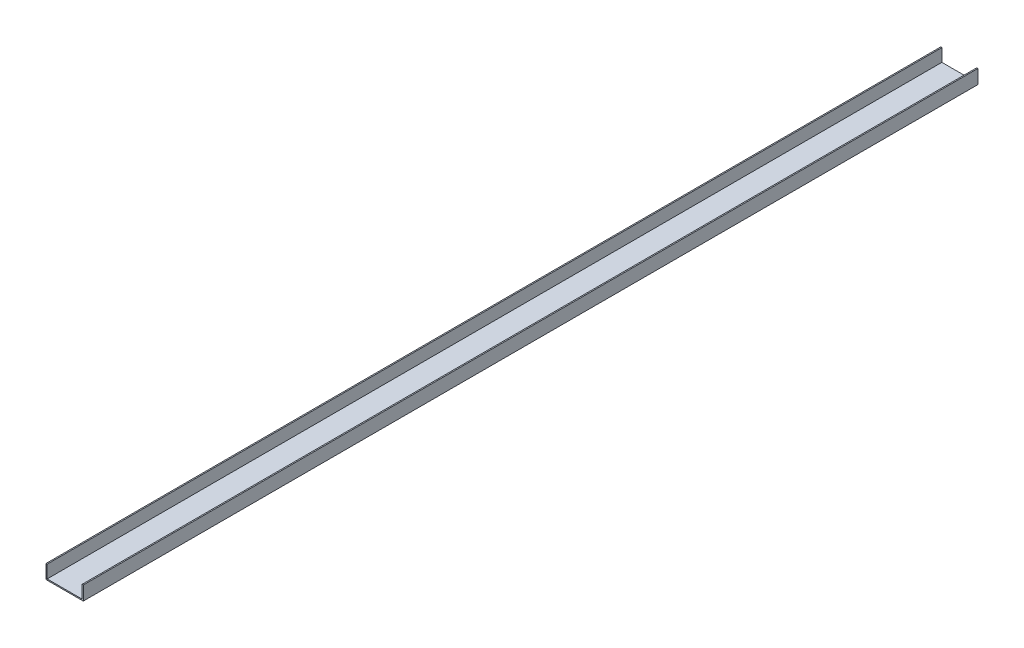
SolidWorks part; units mm, degrees
ref_plane "Front" through (0, 0, 0) normal (0, 0, 1) x (1, 0, 0)
ref_plane "Top" through (0, 0, 0) normal (0, 1, 0) x (1, 0, 0)
ref_plane "Right" through (0, 0, 0) normal (1, 0, 0) x (0, 0, -1)
sketch "Sketch1" plane through (0, 0, 0) normal (0, 0, 1) x (1, 0, 0)
  line L0 (0, -9.525) -> (0, 9.525) construction
  line L1 (-25.4, 0) -> (25.4, 0) construction
  line L2 (23.8125, 9.525) -> (-23.8125, 9.525) construction
  line L3 (-25.4, -9.525) -> (25.4, -9.525)
  line L4 (-25.4, -9.525) -> (-25.4, 9.525)
  line L5 (-25.4, 9.525) -> (25.4, 9.525)
  line L6 (25.4, -9.525) -> (25.4, 9.525)
  line L7 (-25.4, -9.525) -> (25.4, 9.525) construction
  line L8 (-25.4, 9.525) -> (25.4, -9.525) construction
  line L9 (-23.8125, -9.525) -> (23.8125, -9.525)
  point P3 (0, 0)
  point P4 (0, 0)
  point P8 (0, 0)
  point P13 (25.4, -7.9375)
  point P17 (0, 9.525)
  point P20 (0, -9.525)
  dimension "Outside Width" = 50.8
  dimension "Outside Height" = 19.05
  dimension "Inside Height" = 17.4625
  dimension "Wall Thickness" = 1.5875
  dimension "Inside Width" = 47.625
sketch "Sketch2" plane through (0, 0, 0) normal (1, 0, 0) x (0, 0, -1)
  line L0 (-609.6, 0) -> (609.6, 0) construction
  dimension "Length" = 1219.2
sketch "Sketch3" plane through (0, 0, 0) normal (0, 0, 1) x (1, 0, 0)
  line L0 (-25.4, 9.525) -> (-25.4, -9.525)
  line L1 (-25.4, -9.525) -> (25.4, -9.525)
  line L2 (25.4, -9.525) -> (25.4, 9.525)
  line L3 (25.4, 9.525) -> (23.8125, 9.525)
  line L4 (23.8125, 9.525) -> (23.8125, -7.9375)
  line L5 (23.8125, -7.9375) -> (-23.8125, -7.9375)
  line L6 (-23.8125, -7.9375) -> (-23.8125, 9.525)
  line L7 (-23.8125, 9.525) -> (-25.4, 9.525)
  line L8 (-23.8125, -7.9375) -> (-23.8125, -9.525) construction
  dimension "D1" = 19.05
  dimension "D2" = 50.8
  dimension "D3" = 1.5875
extrude "Boss-Extrude2" add sketch "Sketch3" along normal mid plane 1219.2
sketch "Reference Sketch1" plane through (0, 0, 0) normal (1, 0, 0) x (0, 0, -1)
  line L0 (-609.6, 0) -> (609.6, 0) construction
  point P0 (-576.2625, 0)
  point P1 (576.2625, 0)
  dimension "D1" = 33.3375
  dimension "D2" = 33.3375
equation "\"D1@Sketch3\" = \"Outside Height@Sketch1\""
equation "\"D2@Sketch3\" = \"Outside Width@Sketch1\""
equation "\"D3@Sketch3\" = \"Wall Thickness@Sketch1\""
equation "\"D1@Reference Sketch1\"=\"Outside Height@Sketch1\" * 1.75"
equation "\"D2@Reference Sketch1\" = \"D1@Reference Sketch1\""
equation "\"D1@Boss-Extrude2\" = \"Length@Sketch2\""
equation "\"Inside Height@Sketch1\"=\"Outside Height@Sketch1\"-\"Wall Thickness@Sketch1\""
equation "\"Inside Width@Sketch1\"=\"Outside Width@Sketch1\"-\"Wall Thickness@Sketch1\"*2"
